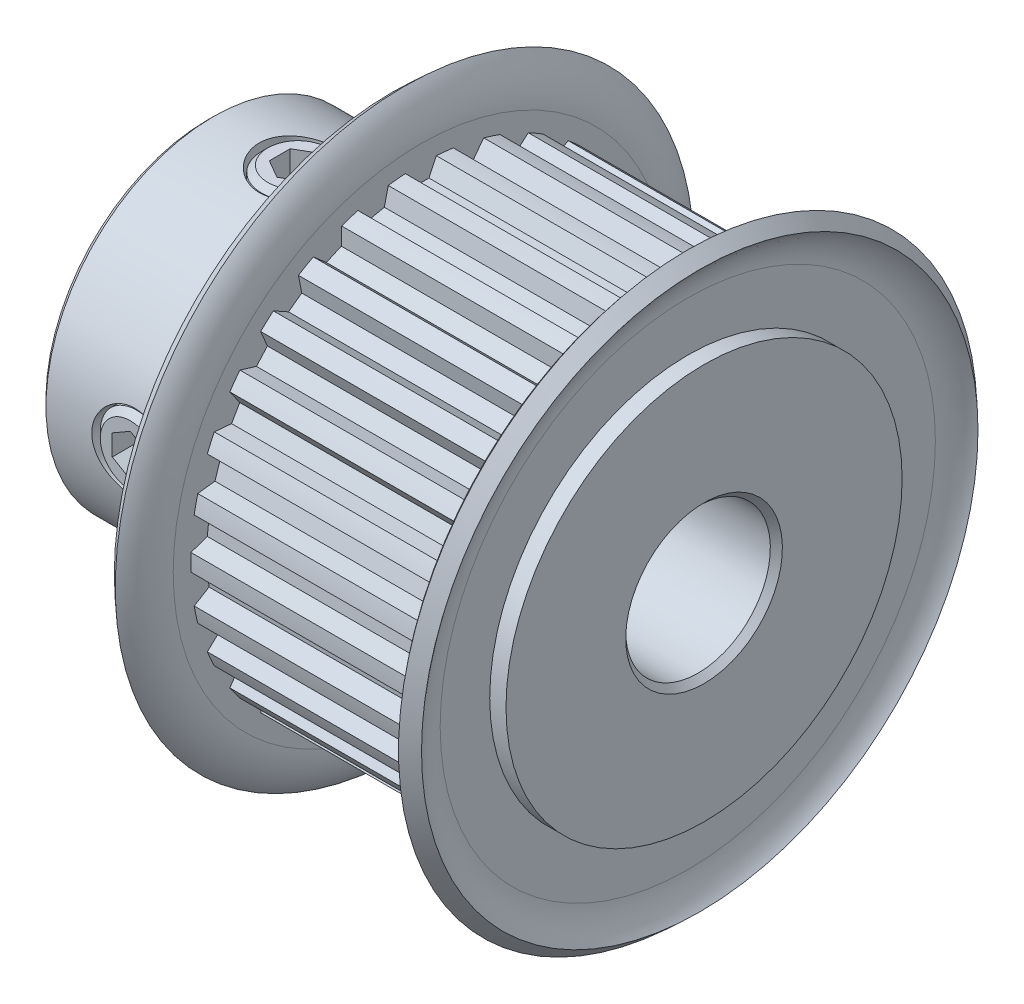
SolidWorks part; units mm, degrees
ref_plane "Front Plane" through (0, 0, 0) normal (0, 0, 1) x (1, 0, 0)
ref_plane "Top Plane" through (0, 0, 0) normal (0, 1, 0) x (1, 0, 0)
ref_plane "Right Plane" through (0, 0, 0) normal (1, 0, 0) x (0, 0, -1)
sketch "Sketch2" plane through (0, 0, 0) normal (1, 0, 0) x (0, 0, -1)
  line L3 (0, 0) -> (0, 8.8745) construction
  line L6 (0, -9.3825) -> (0, -9.7) construction
  line L7 (-0.5715, 9.3651) -> (-0.3397, 8.868)
  line L8 (0.5715, 9.3651) -> (0.3397, 8.868)
  line L9 (-0.5715, 9.3651) -> (-0.6435, 9.5195)
  line L10 (0.5715, 9.3651) -> (0.6435, 9.5195)
  line L12 (-0.3397, 8.868) -> (0.3397, 8.868)
  line L14 (0, 9.3825) -> (0, 9.7) construction
  line L15 (0, 0) -> (0, -1.143) construction
  circle A0 centre (0, 0) radius 9.7 construction
  circle A1 centre (0, 0) radius 8.8745 construction
  circle A2 centre (0, 0) radius 9.3825 construction
  arc A7 (0.6435, 9.5195) -> (-0.6435, 9.5195) centre (0, 0) ccw
  point P5 (0, 9.5412)
  dimension "D3" = 0.3175
  dimension "D1" = 50
sketch "Sketch1" plane through (0, 0, 0) normal (0, 0, 1) x (1, 0, 0)
  line L0 (-10.3, 0) -> (10.3, 0) construction
  line L1 (-10.3, 3) -> (10.3, 3)
  line L2 (-10.3, 3) -> (-10.3, 6.95)
  line L3 (-2.8, 12) -> (-2.125, 12)
  line L4 (-1.45, 9.7) -> (-1.45, 10.2715)
  line L5 (-1.45, 10.843) -> (-1.45, 9.7) construction
  line L6 (-1.45, 9.7) -> (8.95, 9.7)
  line L7 (8.95, 9.7) -> (8.95, 10.2715)
  line L8 (8.95, 9.7) -> (10.3, 9.7) construction
  line L9 (9.625, 12) -> (10.3, 12)
  line L10 (10.3, 12) -> (10.3, 3)
  line L11 (9.625, 9.7) -> (9.625, 12) construction
  line L12 (-6.55, 6.95) -> (-6.55, 3) construction
  line L13 (-2.8, 12) -> (-2.8, 6.95)
  line L14 (-2.8, 6.95) -> (-10.3, 6.95)
  arc A0 (8.95, 10.2715) -> (9.625, 12) centre (11.5006, 10.2715) cw
  arc A1 (-1.45, 10.2715) -> (-2.125, 12) centre (-4.0006, 10.2715) ccw
  point P20 (3.75, 9.7)
  dimension "Bore Size" = 6
  dimension "Overall Width" = 20.6
  dimension "Inside Width" = 10.4
  dimension "OD" = 24
  dimension "D2" = 19.4
  dimension "D3" = 1.143
  dimension "D4" = 0.5715
  dimension "Outside Width" = 13.1
revolve "Revolve1" add sketch "Sketch1" angle 360 mid plane about L0
sketch "Sketch4" plane through (-1.45, 0, 0) normal (1, 0, 0) x (0, 0, -1)
  circle A0 centre (0, 0) radius 9.5413
  circle A2 centre (0, 0) radius 9.7
  circle A3 centre (0, 0) radius 9.7 construction
extrude "Cut-Extrude2" cut sketch "Sketch4" along normal up to surface (10.4 mm away) up to face at (8.95, -9.7, 0)
sketch "Sketch3" plane through (-1.45, 0, 0) normal (1, 0, 0) x (0, 0, -1)
  line L2 (-0.5715, 9.3651) -> (-0.3397, 8.868) construction
  line L3 (-0.3397, 8.868) -> (0.3397, 8.868) construction
  line L4 (0.5715, 9.3651) -> (0.3397, 8.868) construction
  line L5 (-0.6435, 9.5195) -> (-0.3397, 8.868)
  line L6 (-0.3397, 8.868) -> (0.3397, 8.868)
  line L7 (0.6435, 9.5195) -> (0.3397, 8.868)
  arc A1 (0.6435, 9.5195) -> (-0.6435, 9.5195) centre (0, 0) ccw construction
  arc A2 (0.6435, 9.5195) -> (-0.6435, 9.5195) centre (0, 0) ccw
extrude "Cut-Extrude1" cut sketch "Sketch3" along normal up to surface (10.4 mm away)
pattern_circular "CirPattern1" count 30 over 360 about axis through (0, 0, 0) along (1, 0, 0) of "Cut-Extrude1"
sketch "Sketch6" plane through (0, 0, 0) normal (0, 1, 0) x (1, 0, 0)
  line L0 (-10.3, 0) -> (-8.05, 0) construction
  line L2 (-2.8, 0) -> (-5.05, 0) construction
  line L5 (-6.55, 0) -> (-7.6107, -1.0607) construction
  circle A0 centre (-6.55, 0) radius 1.5 construction
  circle A1 centre (-6.55, 0) radius 1.6
  dimension "D1" = 0.1
  dimension "D2" = 45
  dimension "SS Dia" = 3
extrude "Cut-Extrude3" cut sketch "Sketch6" along normal through all
sketch "Sketch7" plane through (0, 0, 0) normal (0, 0, 1) x (1, 0, 0)
  line L0 (-7.796, 6.95) -> (-6.55, 6.95)
  line L1 (-8.05, 6.696) -> (-8.05, 3.635)
  line L2 (-8.05, 3.635) -> (-7.796, 3.381)
  line L3 (-7.796, 3.381) -> (-6.55, 3.381)
  line L4 (-6.55, 3.381) -> (-6.55, 6.95) construction
  line L5 (-2.8, 6.95) -> (-10.3, 6.95) construction
  line L6 (-8.05, 6.696) -> (-7.796, 6.95)
  line L8 (-6.55, 6.95) -> (-6.55, 3.381)
  point P0 (-8.05, 6.95)
  point P4 (-8.05, 3.381)
  dimension "D2" = 0.381
revolve "Revolve2" add sketch "Sketch7" angle 360 mid plane about L4
sketch "Sketch8" plane through (0, 6.95, 0) normal (0, 1, 0) x (1, 0, 0)
  line L0 (-6.55, 0) -> (-6.55, 1.5) construction
  line L1 (-6.55, 0.866) -> (-7.3, 0.433)
  line L2 (-7.3, 0.433) -> (-7.3, -0.433)
  line L3 (-7.3, -0.433) -> (-6.55, -0.866)
  line L4 (-6.55, -0.866) -> (-5.8, -0.433)
  line L5 (-5.8, -0.433) -> (-5.8, 0.433)
  line L6 (-5.8, 0.433) -> (-6.55, 0.866)
  circle A0 centre (-6.55, 0) radius 0.75 construction
  circle A1 centre (-6.55, 0) radius 1.5 construction
  point P16 (-6.55, 0.75)
extrude "Cut-Extrude4" cut sketch "Sketch8" against normal blind 1.016
pattern_circular "CirPattern2" count 2 over 90 about axis through (-10.3, 0, 0) along (-1, 0, 0) of "Cut-Extrude3"
pattern_circular "CirPattern3" count 2 over 90 about axis through (0, 0, 0) along (1, 0, 0) of bodies 107
sketch "Sketch5" plane through (0, 0, 0) normal (0, 0, 1) x (1, 0, 0)
  line L1 (8.95, 10.2715) -> (8.95, -10.2715) construction
  line L5 (-1.45, -10.2715) -> (-1.45, 10.2715) construction
  line L6 (-1.45, -10.2715) -> (-1.45, 10.2715) construction
  line L7 (8.95, 10.2715) -> (8.95, -10.2715) construction
  line L8 (-8.05, 0) -> (-6.55, 0) construction
  line L9 (-6.55, 0) -> (-7.6107, -1.0607) construction
  circle A0 centre (-6.55, 0) radius 1.5 construction
  circle A1 centre (-6.55, 0) radius 1.5 construction
  point P0 (8.95, 0)
  point P10 (-7.6107, -1.0607)
  dimension "D1" = 45
sketch "Sketch10" plane through (0, 0, 0) normal (0, 1, 0) x (1, 0, 0)
  line L0 (-2.8, 12) -> (-2.8, -12) construction
  line L1 (-2.8, 12) -> (-2.8, -12)
chamfer "Chamfer1" distance 0.25 angle 45 3 edges at (-10.3, -6.95, 0) (10.3, -3, 0) (-10.3, -3, 0)
sketch "Sketch9" plane through (0, 0, 0) normal (0, 0, 1) x (1, 0, 0)
  line L0 (-10.3, 0) -> (10.3, 0) construction
  line L3 (9.625, 12) -> (10.1214, 11.5426)
  line L4 (9.625, 10.2715) -> (9.625, 8.2165)
  line L5 (-1.45, 8.2165) -> (9.625, 8.2165) construction
  line L6 (9.625, 8.2165) -> (10.3, 8.2165)
  line L7 (10.3, 12) -> (10.3, 3) construction
  line L8 (10.3, 8.2165) -> (10.3, 12)
  line L9 (9.625, 12) -> (9.935, 12.3364)
  line L10 (9.935, 12.3364) -> (10.3, 12)
  line L11 (-1.45, 9.5195) -> (-1.45, 8.868) construction
  line L12 (-1.45, 8.868) -> (-1.45, 8.2165) construction
  arc A0 (10.1214, 11.5426) -> (9.625, 10.2715) centre (11.5006, 10.2715) ccw
  arc A2 (9.625, 12) -> (8.95, 10.2715) centre (11.5006, 10.2715) ccw construction
revolve "Cut-Revolve1" cut sketch "Sketch9" angle 360 about L0
ref_plane "Plane1" through (3.75, 0, 0) normal (1, 0, 0) x (0, 0, -1)
mirror "Mirror1" about plane through (3.75, 0, 0) normal (1, 0, 0) of "Cut-Revolve1"
equation "\"D3@Sketch2\" = (\"hs@Sketch2\"-\"ht@Sketch2\")/2"
equation "\"D2@Sketch1\" = \"PD@Sketch2\""
equation "\"D3@Sketch1\" = \"hs@Sketch2\""
equation "\"D4@Sketch1\" = \"D3@Sketch1\"/2"
